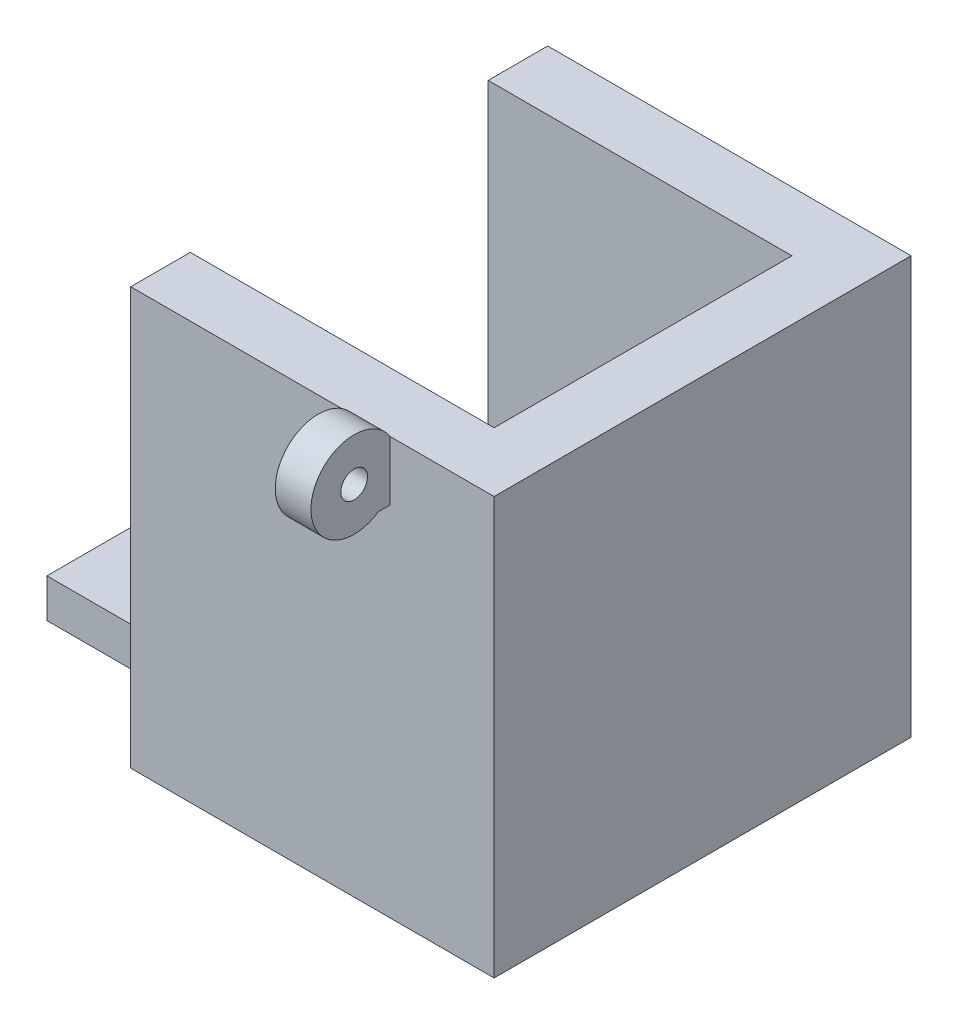
SolidWorks part; units mm, degrees
ref_plane "前基準面" through (0, 0, 0) normal (0, 0, 1) x (1, 0, 0)
ref_plane "上基準面" through (0, 0, 0) normal (0, 1, 0) x (1, 0, 0)
ref_plane "右基準面" through (0, 0, 0) normal (1, 0, 0) x (0, 0, -1)
sketch "草圖1" plane through (0, 0, 0) normal (0, 1, 0) x (1, 0, 0)
  line L1 (-109.4634, 62.6098) -> (162.5366, 62.6098)
  line L2 (-109.4634, 62.6098) -> (-109.4634, -77.3902)
  line L3 (-109.4634, -77.3902) -> (162.5366, -77.3902)
  line L4 (162.5366, 62.6098) -> (162.5366, -77.3902)
  dimension "D1" = 272
  dimension "D2" = 140
extrude "填料-伸長1" add sketch "草圖1" along normal blind 140
sketch "草圖2" plane through (0, 140, 0) normal (0, 1, 0) x (1, 0, 0)
  line L0 (-109.4634, 62.6098) -> (-109.4634, -77.3902) construction
  line L1 (-109.4634, 42.6098) -> (142.5366, 42.6098)
  line L2 (-109.4634, 42.6098) -> (-109.4634, -57.3902)
  line L3 (-109.4634, -57.3902) -> (142.5366, -57.3902)
  line L4 (142.5366, 42.6098) -> (142.5366, -57.3902)
  line L5 (162.5366, 62.6098) -> (-109.4634, 62.6098) construction
  line L6 (-109.4634, -77.3902) -> (162.5366, -77.3902) construction
  line L7 (162.5366, -77.3902) -> (162.5366, 62.6098) construction
  dimension "D1" = 20
  dimension "D2" = 20
  dimension "D3" = 20
extrude "除料-伸長1" cut sketch "草圖2" against normal blind 110
sketch "草圖8" plane through (0, 0, 77.3902) normal (0, 0, 1) x (1, 0, 0)
  line L0 (162.5366, 140) -> (162.5366, 0) construction
  line L1 (115.5366, 132) -> (127.5366, 132)
  line L2 (115.5366, 132) -> (115.5366, 120)
  line L3 (115.5366, 120) -> (127.5366, 120)
  line L4 (127.5366, 132) -> (127.5366, 120)
  line L5 (-109.4634, 140) -> (162.5366, 140) construction
  dimension "D1" = 35
  dimension "D2" = 8
  dimension "D3" = 12
  dimension "D4" = 12
extrude "填料-伸長2" add sketch "草圖8" along normal blind 10
sketch "草圖9" plane through (127.5366, 0, 0) normal (1, 0, 0) x (0, 0, -1)
  line L0 (-87.3902, 132) -> (-89.3902, 132) construction
  circle A0 centre (-89.3902, 132) radius 4.49
  dimension "D1" = 8.98
extrude "伸長-薄件1" add sketch "草圖9" against normal blind 12 thin
sketch "草圖11" plane through (127.5366, 0, 0) normal (1, 0, 0) x (0, 0, -1)
  line L0 (-1093.8802, 132) -> (48906.1198, 132) construction
  line L1 (-89.3902, -872.49) -> (-89.3902, 49127.51) construction
  circle A2 centre (-89.3902, 132) radius 4.49
  dimension "D1" = 8.98
extrude "除料-伸長5" cut sketch "草圖11" against normal through all
sketch "草圖13" plane through (0, 140, 0) normal (0, 1, 0) x (1, 0, 0)
  line L0 (162.5366, 62.6098) -> (-109.4634, 62.6098) construction
  line L1 (-109.4634, -77.3902) -> (40.5366, -77.3902)
  line L2 (-109.4634, -77.3902) -> (-109.4634, 62.6098)
  line L3 (-109.4634, 62.6098) -> (40.5366, 62.6098)
  line L4 (40.5366, -77.3902) -> (40.5366, 62.6098)
  dimension "D1" = 150
extrude "除料-伸長7" cut sketch "草圖13" against normal through all
sketch "草圖14" plane through (40.5366, 0, 0) normal (-1, 0, 0) x (0, 0, 1)
  line L0 (-62.6098, 0) -> (-62.6098, 140) construction
  line L1 (-42.6098, 20) -> (55.5296, 20)
  line L2 (-42.6098, 20) -> (-42.6098, 7)
  line L3 (-42.6098, 7) -> (55.5296, 7)
  line L4 (55.5296, 20) -> (55.5296, 7)
  line L5 (57.3902, 30) -> (-42.6098, 30) construction
  line L6 (77.3902, 0) -> (-62.6098, 0) construction
  dimension "D1" = 20
  dimension "D2" = 10
  dimension "D3" = 7
extrude "填料-伸長3" add sketch "草圖14" along normal blind 50
sketch "草圖15" plane through (0, 20, 0) normal (0, 1, 0) x (1, 0, 0)
  line L0 (40.5366, -7.3902) -> (10.5366, -7.3902) construction
  line L1 (40.5366, -57.3902) -> (40.5366, 42.6098) construction
  circle A0 centre (10.5366, -7.3902) radius 3
  dimension "D1" = 6
extrude "除料-伸長8" cut sketch "草圖15" against normal through all
